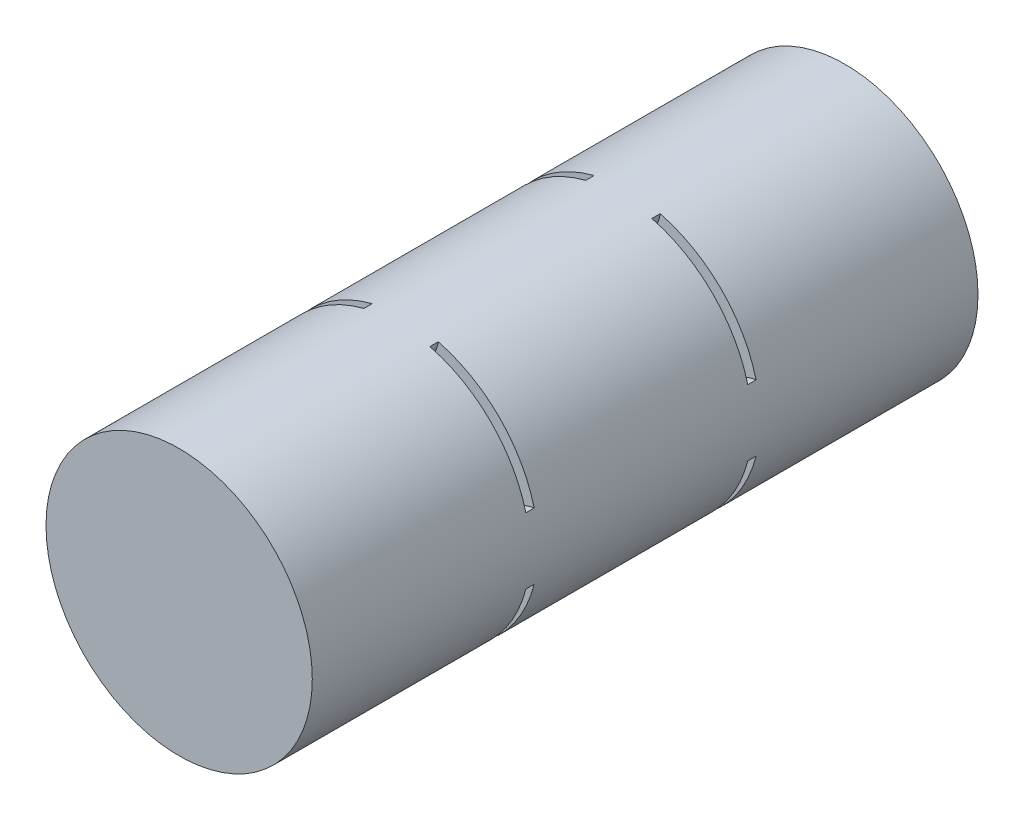
SolidWorks part; units mm, degrees
material "Water"
ref_plane "Front Plane" through (0, 0, 0) normal (0, 0, 1) x (1, 0, 0)
ref_plane "Top Plane" through (0, 0, 0) normal (0, 1, 0) x (1, 0, 0)
ref_plane "Right Plane" through (0, 0, 0) normal (1, 0, 0) x (0, 0, -1)
sketch "Sketch1" plane through (0, 0, 0) normal (0, 0, 1) x (1, 0, 0)
  circle A0 centre (0, 0) radius 50.8
  dimension "D1" = 101.6
extrude "Boss-Extrude1" add sketch "Sketch1" along normal blind 254
sketch "Sketch2" plane through (0, 0, 254) normal (0, 0, 1) x (1, 0, 0)
  circle A0 centre (0, 50.8) radius 12.7 construction
  circle A1 centre (0, 0) radius 50.8 construction
  circle A2 centre (0, 0) radius 19.05
  circle A3 centre (50.8, 0) radius 12.7 construction
  circle A4 centre (0, -50.8) radius 12.7 construction
  circle A5 centre (-50.8, 0) radius 12.7 construction
  arc A6 (-12.6004, 49.2125) -> (-49.2125, 12.6004) centre (0, 0) ccw
  arc A7 (-49.2125, 12.6004) -> (-49.2125, -12.6004) centre (-50.8, 0) cw
  arc A8 (12.6004, 49.2125) -> (-12.6004, 49.2125) centre (0, 50.8) cw
  arc A9 (49.2125, 12.6004) -> (12.6004, 49.2125) centre (0, 0) ccw
  arc A10 (49.2125, -12.6004) -> (49.2125, 12.6004) centre (50.8, 0) cw
  arc A11 (12.6004, -49.2125) -> (49.2125, -12.6004) centre (0, 0) ccw
  arc A12 (-12.6004, -49.2125) -> (12.6004, -49.2125) centre (0, -50.8) cw
  arc A13 (-49.2125, -12.6004) -> (-12.6004, -49.2125) centre (0, 0) ccw
  point P16 (0, 0)
  point P32 (0, 0)
  dimension "D1" = 25.4
  dimension "D2" = 38.1
  dimension "D3" = 4
  dimension "D4" = 4
extrude "Cut-Extrude1" cut sketch "Sketch2" against normal blind 3.175 from offset 83.0783 offset against normal yes
sketch "Sketch4" plane through (0, 0, 0) normal (0, 0, 1) x (1, 0, 0)
  circle A0 centre (0, 50.8) radius 12.7 construction
  circle A2 centre (0, 0) radius 19.05
  circle A3 centre (50.8, 0) radius 12.7 construction
  circle A4 centre (0, -50.8) radius 12.7 construction
  circle A5 centre (-50.8, 0) radius 12.7 construction
  arc A6 (-12.6004, 49.2125) -> (-49.2125, 12.6004) centre (0, 0) ccw
  arc A7 (-49.2125, 12.6004) -> (-49.2125, -12.6004) centre (-50.8, 0) cw
  arc A8 (12.6004, 49.2125) -> (-12.6004, 49.2125) centre (0, 50.8) cw
  arc A9 (49.2125, 12.6004) -> (12.6004, 49.2125) centre (0, 0) ccw
  arc A10 (49.2125, -12.6004) -> (49.2125, 12.6004) centre (50.8, 0) cw
  arc A11 (12.6004, -49.2125) -> (49.2125, -12.6004) centre (0, 0) ccw
  arc A12 (-12.6004, -49.2125) -> (12.6004, -49.2125) centre (0, -50.8) cw
  arc A13 (-49.2125, -12.6004) -> (-12.6004, -49.2125) centre (0, 0) ccw
  point P16 (0, 0)
  point P32 (0, 0)
  dimension "D1" = 25.4
  dimension "D2" = 38.1
  dimension "D3" = 4
  dimension "D4" = 4
extrude "Cut-Extrude2" cut sketch "Sketch4" along normal blind 3.175 from offset 83.0783
